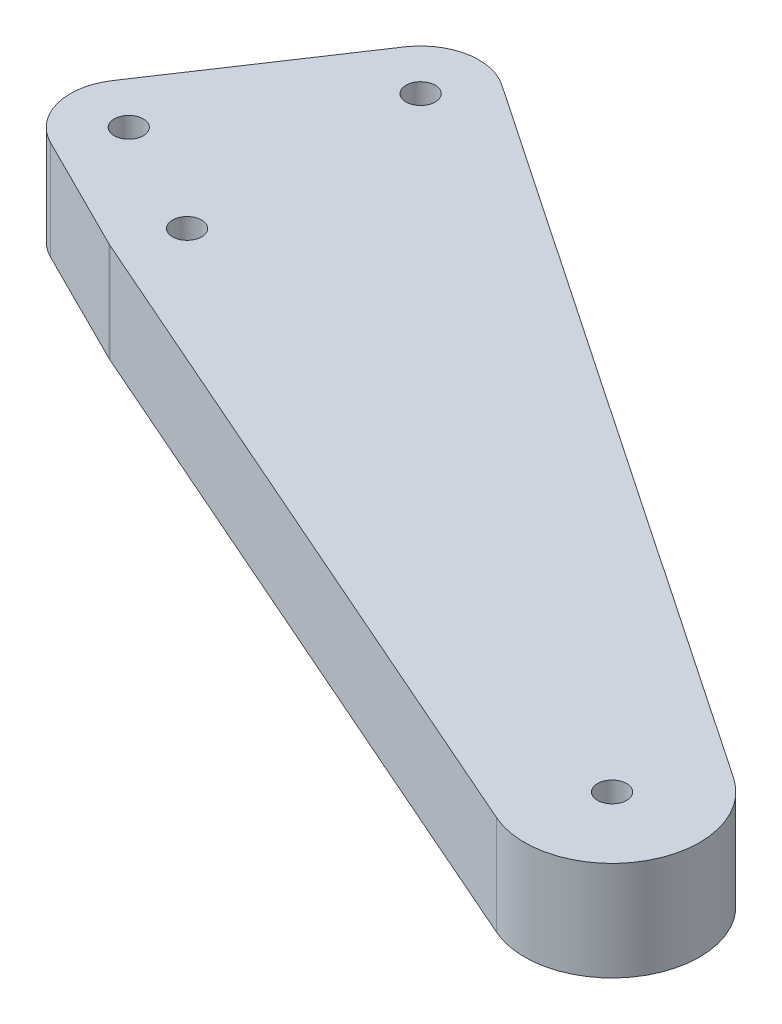
SolidWorks part; units mm, degrees
ref_plane "Front Plane" through (0, 0, 0) normal (0, 0, 1) x (1, 0, 0)
ref_plane "Top Plane" through (0, 0, 0) normal (0, 1, 0) x (1, 0, 0)
ref_plane "Right Plane" through (0, 0, 0) normal (1, 0, 0) x (0, 0, -1)
sketch "Sketch1" plane through (0, 0, 0) normal (0, 1, 0) x (1, 0, 0)
  line L1 (5.6025, 48.2832) -> (128.4037, -34.7751)
  line L2 (113.9723, -60.9356) -> (-4.0185, -9.1571)
  line L4 (-8.3205, 45.547) -> (-28.3205, 15.547)
  line L5 (-24.4721, 1.0557) -> (-4.4721, -8.9443)
  arc A0 (-8.3205, 45.547) -> (5.6025, 48.2832) centre (0, 40) cw
  arc A1 (128.4037, -34.7751) -> (113.9723, -60.9356) centre (120, -47.2) cw
  arc A2 (-4.0185, -9.1571) -> (-4.4721, -8.9443) centre (0, 0) cw
  arc A3 (-28.3205, 15.547) -> (-24.4721, 1.0557) centre (-20, 10) ccw
  dimension "D1" = 10
  dimension "D2" = 10
  dimension "D3" = 15
  dimension "D9" = 10
  dimension "D4" = 87.2
  dimension "D5" = 40
  dimension "D6" = 120
  dimension "D7" = 20
  dimension "D8" = 30
extrude "Boss-Extrude1" add sketch "Sketch1" along normal blind 17
sketch "Sketch2" plane through (0, 17, 0) normal (0, 1, 0) x (1, 0, 0)
  circle A0 centre (0, 40) radius 2.5
  circle A1 centre (0, 0) radius 2.5
  circle A2 centre (120, -47.2) radius 2.5
  circle A3 centre (-20, 10) radius 2.5
  arc A4 (-28.3205, 15.547) -> (-24.4721, 1.0557) centre (-20, 10) ccw construction
  dimension "D1" = 5
  dimension "D2" = 5
extrude "Cut-Extrude1" cut sketch "Sketch2" against normal through all
